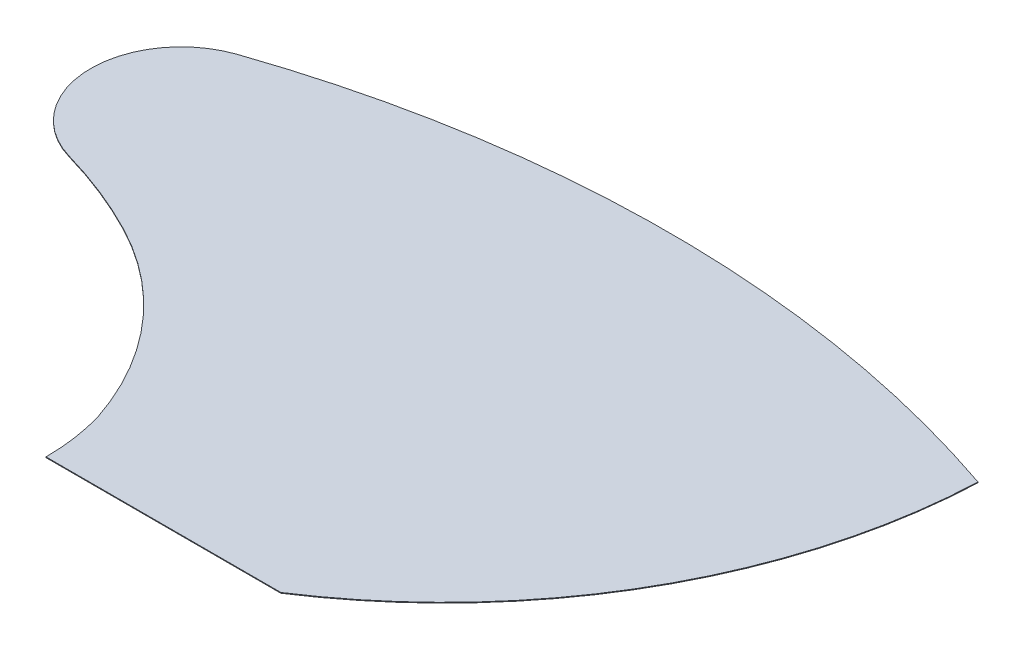
SolidWorks part; units mm, degrees
ref_plane "Front Plane" through (0, 0, 0) normal (0, 0, 1) x (1, 0, 0)
ref_plane "Top Plane" through (0, 0, 0) normal (0, 1, 0) x (1, 0, 0)
ref_plane "Right Plane" through (0, 0, 0) normal (1, 0, 0) x (0, 0, -1)
sketch "Sketch2"
sketch "Sketch1" plane through (0, 0, 0) normal (0, 1, 0) x (1, 0, 0)
  line L2 (-44.0512, 146.9643) -> (109.5118, 146.9643) construction
  line L3 (77.0118, 6.9643) -> (142.0118, 6.9643)
  line L6 (-9.8882, 176.2745) -> (-9.8882, 105.631) construction
  line L8 (127.0118, 146.5764) -> (123.4206, 101.72) construction
  line L9 (107.0756, 148.1725) -> (146.948, 144.9804) construction
  line L10 (117.0437, 147.3745) -> (125.0167, 121.6562) construction
  line L11 (125.0167, 121.6562) -> (136.9799, 145.7784) construction
  line L12 (107.0756, 148.1725) -> (123.4206, 101.72) construction
  line L13 (123.4206, 101.72) -> (146.948, 144.9804) construction
  arc A14 (7.0118, 129.9168) -> (212.0118, 129.9168) centre (109.5118, -169.7057) cw
  arc A17 (142.0118, 6.9643) -> (212.0118, 129.9168) centre (57.9998, 136.1971) ccw
  arc A22 (7.0118, 129.9168) -> (8.217, 82.2299) centre (15.1038, 106.2626) ccw
  arc A28 (8.217, 82.2299) -> (33.0398, 72.3535) centre (-28.793, -46.9219) cw
  arc A30 (33.0398, 72.3535) -> (74.6261, 23.6723) centre (-6.1355, -3.2157) cw
  arc A31 (74.6261, 23.6723) -> (77.0118, 6.9643) centre (16.9018, 6.9058) cw
  point P6 (109.5118, 6.9643)
  point P19 (125.0167, 121.6562)
  point P20 (117.0437, 147.3745)
  point P21 (109.5118, 146.9643)
  point P23 (136.9799, 145.7784)
  dimension "D1" = 25
  dimension "D2" = 154.14
  dimension "D3" = 221.9
  dimension "D6" = 60.11
  dimension "D8" = 70
  dimension "D7" = 85.12
  dimension "D15" = 134.35
  dimension "D4" = 140
  dimension "D5" = 65
  dimension "D9" = 85
  dimension "D10" = 40
  dimension "D11" = 45
  dimension "D12" = 25
  dimension "D13" = 10
  dimension "D14" = 10
extrude "Boss-Extrude1" add sketch "Sketch1" along normal blind 0.2
